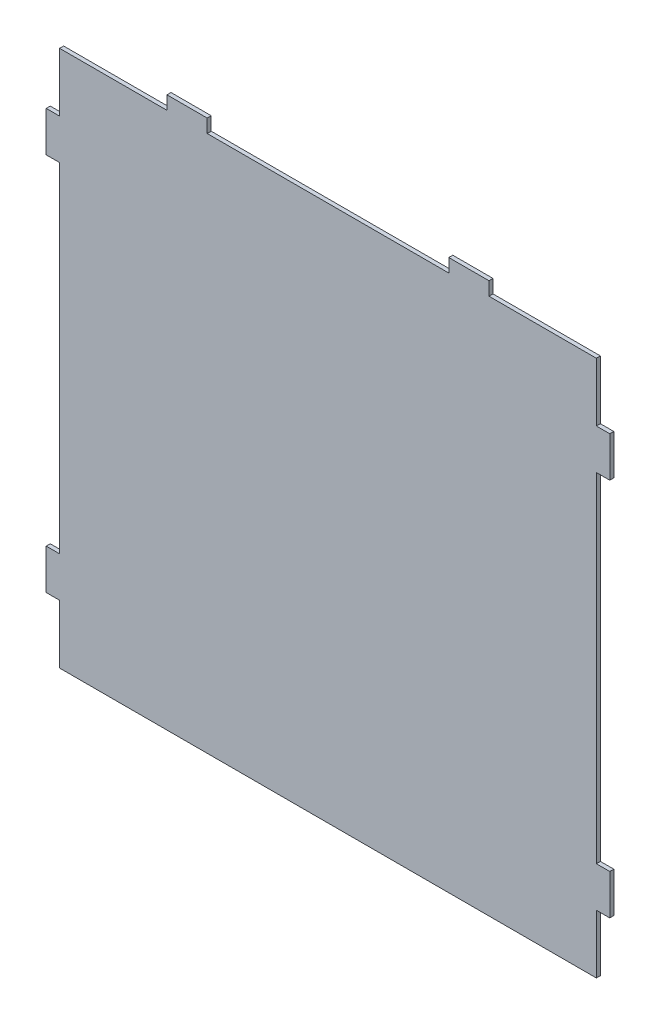
SolidWorks part; units mm, degrees
ref_plane "Alzado" through (0, 0, 0) normal (0, 0, 1) x (1, 0, 0)
ref_plane "Planta" through (0, 0, 0) normal (0, 1, 0) x (1, 0, 0)
ref_plane "Vista lateral" through (0, 0, 0) normal (1, 0, 0) x (0, 0, -1)
sketch "Croquis1" plane through (0, 0, 0) normal (0, 0, 1) x (1, 0, 0)
  line L0 (-200, 0) -> (200, 0) construction
  line L1 (-200, 200) -> (200, 200)
  line L2 (-200, 200) -> (-200, -200)
  line L3 (-200, -200) -> (200, -200)
  line L4 (200, 200) -> (200, -200)
  line L5 (-200, 200) -> (200, -200) construction
  line L6 (-200, -200) -> (200, 200) construction
  line L7 (-200, 126.2437) -> (-200, 156.2437)
  line L8 (-200, 126.2437) -> (-210, 126.2437)
  line L9 (-200, 156.2437) -> (-210, 156.2437)
  line L10 (-210, 126.2437) -> (-210, 156.2437)
  line L11 (-200, -126.2437) -> (-200, -156.2437)
  line L12 (-200, -126.2437) -> (-210, -126.2437)
  line L13 (-210, -126.2437) -> (-210, -156.2437)
  line L14 (-200, -156.2437) -> (-210, -156.2437)
  line L15 (0, 200) -> (0, -200) construction
  line L16 (200, -126.2437) -> (210, -126.2437)
  line L17 (200, -126.2437) -> (200, -156.2437)
  line L18 (200, -156.2437) -> (210, -156.2437)
  line L19 (210, -126.2437) -> (210, -156.2437)
  line L20 (210, 126.2437) -> (210, 156.2437)
  line L21 (210, 126.2437) -> (200, 126.2437)
  line L22 (210, 156.2437) -> (200, 156.2437)
  line L23 (200, 156.2437) -> (200, 126.2437)
  line L24 (90, 200) -> (120, 200)
  line L25 (90, 200) -> (90, 210)
  line L26 (120, 200) -> (120, 210)
  line L27 (90, 210) -> (120, 210)
  line L28 (-90, 200) -> (-90, 210)
  line L29 (-90, 200) -> (-120, 200)
  line L30 (-120, 200) -> (-120, 210)
  line L31 (-90, 210) -> (-120, 210)
  point P0 (0, 0)
  dimension "D1" = 400
  dimension "D2" = 400
  dimension "D3" = 10
  dimension "D4" = 30
  dimension "D5" = 10
  dimension "D6" = 30
  dimension "D7" = 80
extrude "Saliente-Extruir1" add sketch "Croquis1" along normal blind 3 contours L4 L1 L2 L3 | L20 L22 L4 L21 | L19 L16 L4 L18 | L14 L2 L12 L13 | L10 L8 L2 L9 | L28 L31 L30 L1 | L27 L25 L1 L26
